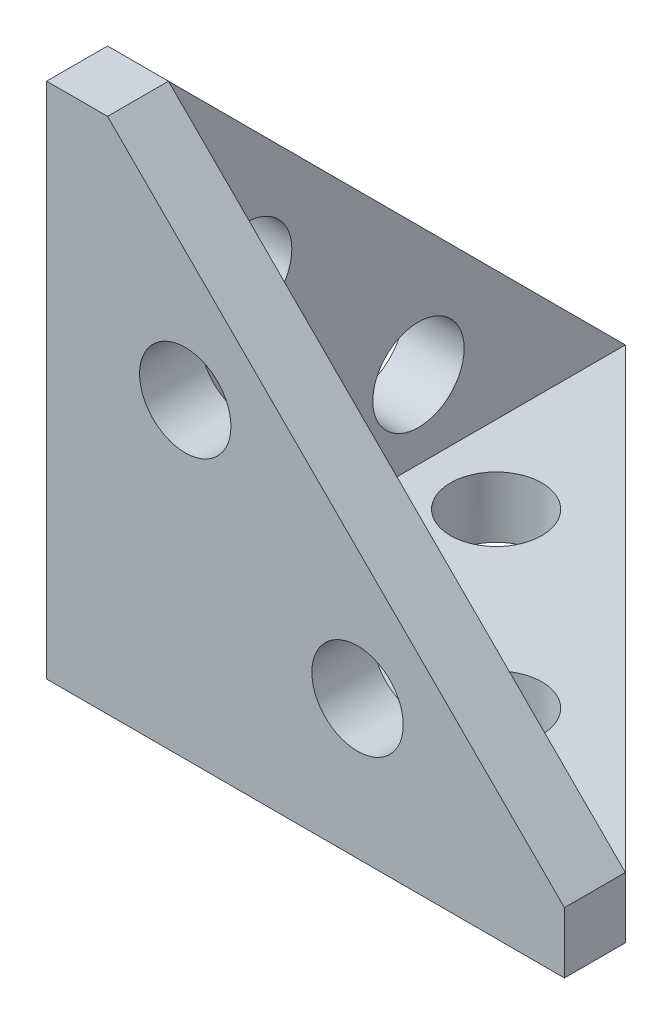
SolidWorks part; units mm, degrees
ref_plane "Ön Düzlem" through (0, 0, 0) normal (0, 0, 1) x (1, 0, 0)
ref_plane "Üst Düzlem" through (0, 0, 0) normal (0, 1, 0) x (1, 0, 0)
ref_plane "Sağ Düzlem" through (0, 0, 0) normal (1, 0, 0) x (0, 0, -1)
sketch "Sketch1" plane through (0, 0, 0) normal (0, 1, 0) x (1, 0, 0)
  line L0 (0, 15) -> (15, 0)
  line L1 (0, 0) -> (15, 0)
  line L2 (0, 0) -> (0, 15)
  dimension "D1" = 15
  dimension "D2" = 15
extrude "Boss-Extrude1" add sketch "Sketch1" along normal blind 2
sketch "Sketch2" plane through (0, 2, 0) normal (0, 1, 0) x (1, 0, 0)
  line L0 (-2, -2) -> (15, -2)
  line L1 (0, 15) -> (-2, 15)
  line L2 (0, 15) -> (0, 0)
  line L4 (-2, 15) -> (-2, -2)
  line L5 (15, -2) -> (15, 0)
  line L6 (15, 0) -> (0, 0)
  dimension "D1" = 2
  dimension "D2" = 2
extrude "Boss-Extrude2" add sketch "Sketch2" along normal blind 15 and the other way blind 2
sketch "Sketch3" plane through (0, 0, 0) normal (1, 0, 0) x (0, 0, -1)
  line L0 (15, 2) -> (0, 17)
  line L1 (0, 17) -> (15, 17)
  line L2 (15, 17) -> (15, 2)
extrude "Cut-Extrude1" cut sketch "Sketch3" against normal blind 15
sketch "Sketch4" plane through (0, 0, 0) normal (0, 0, -1) x (-1, 0, 0)
  line L0 (0, 17) -> (-15, 2)
  line L1 (-15, 2) -> (-15, 17)
  line L2 (-15, 17) -> (0, 17)
extrude "Cut-Extrude2" cut sketch "Sketch4" against normal blind 15
sketch "Sketch5" plane through (0, 0, 0) normal (1, 0, 0) x (0, 0, -1)
  line L0 (0, 12.7574) -> (10.7574, 2) construction
  line L1 (0, 2) -> (0, 17) construction
  line L2 (15, 2) -> (0, 2) construction
  line L3 (0, 17) -> (15, 2) construction
  line L4 (5.3787, 7.3787) -> (7.5, 9.5) construction
  circle A0 centre (2.5503, 10.2071) radius 1.5
  circle A1 centre (8.2071, 4.5503) radius 1.5
  dimension "D2" = 3
  dimension "D1" = 3
  dimension "D3" = 8
extrude "Cut-Extrude3" cut sketch "Sketch5" against normal blind 15
sketch "Sketch6" plane through (0, 0, 0) normal (0, 0, -1) x (-1, 0, 0)
  line L0 (-10.7574, 2) -> (0, 12.7574) construction
  line L1 (-15, 2) -> (0, 2) construction
  line L2 (0, 17) -> (0, 2) construction
  line L3 (-15, 2) -> (0, 17) construction
  line L4 (-5.3787, 7.3787) -> (-7.5, 9.5) construction
  circle A0 centre (-2.5503, 10.2071) radius 1.5
  circle A1 centre (-8.2071, 4.5503) radius 1.5
  dimension "D2" = 3
  dimension "D1" = 3
  dimension "D3" = 8
extrude "Cut-Extrude4" cut sketch "Sketch6" against normal blind 15
sketch "Sketch7" plane through (0, 2, 0) normal (0, 1, 0) x (1, 0, 0)
  line L0 (0, 10.7574) -> (10.7574, 0) construction
  line L1 (0, 15) -> (0, 0) construction
  line L2 (15, 0) -> (0, 0) construction
  line L3 (5.3787, 5.3787) -> (7.5, 7.5) construction
  line L4 (15, 0) -> (0, 15) construction
  circle A0 centre (2.5503, 8.2071) radius 1.5
  circle A1 centre (8.2071, 2.5503) radius 1.5
  dimension "D2" = 3
  dimension "D1" = 3
  dimension "D3" = 8
extrude "Cut-Extrude5" cut sketch "Sketch7" against normal blind 15
